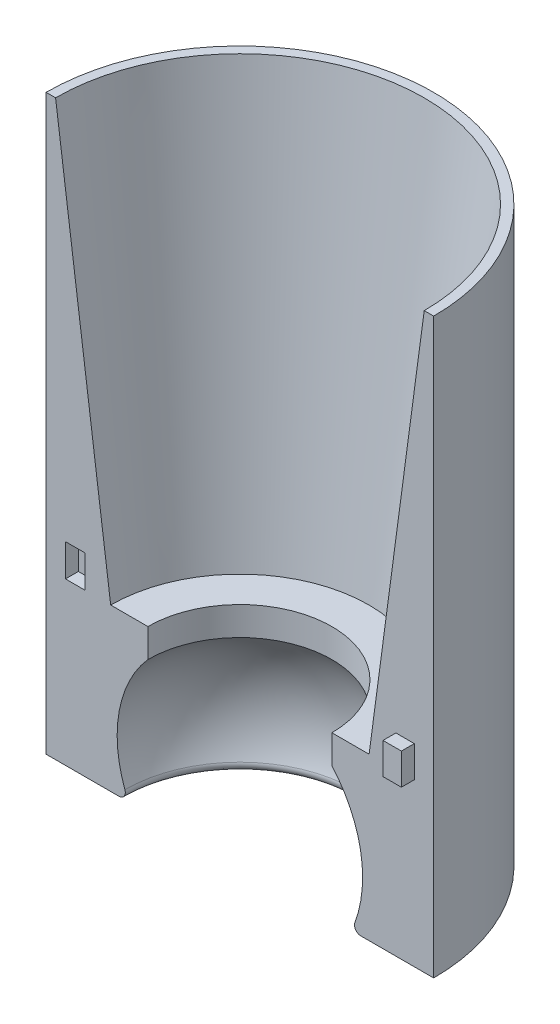
SolidWorks part; units mm, degrees
ref_plane "Front Plane" through (0, 0, 0) normal (0, 0, 1) x (1, 0, 0)
ref_plane "Top Plane" through (0, 0, 0) normal (0, 1, 0) x (1, 0, 0)
ref_plane "Right Plane" through (0, 0, 0) normal (1, 0, 0) x (0, 0, -1)
sketch "Sketch3" plane through (0, 0, 0) normal (0, 0, 1) x (1, 0, 0)
  line L2 (-9.1279, 13.2005) -> (-9.1279, -24.7995)
  line L4 (-9.1279, -13.7995) -> (-39.1279, -13.7995)
  line L5 (-9.1279, -13.7995) -> (-9.1279, 74.9367)
  line L6 (-9.1279, 74.9367) -> (-39.1279, 74.9367)
  line L7 (-39.1279, -13.7995) -> (-39.1279, 74.9367)
  line L8 (-23.3708, 11.2005) -> (-9.1279, 11.2005)
  line L9 (-23.3708, 11.2005) -> (-23.3708, 6.7758)
  line L10 (-9.1279, 95.8585) -> (-9.1279, -91.8555) construction
  line L11 (-23.3708, 11.2005) -> (-29.1283, 11.2005)
  line L12 (-29.1283, 11.2005) -> (-37.6602, 74.9367)
  arc A0 (-9.1279, 13.2005) -> (-9.1279, -24.7995) centre (-9.1279, -5.7995) ccw
  dimension "D5" = 19
  dimension "D1" = 30
  dimension "D2" = 8
  dimension "D3" = 30
  dimension "D4" = 17
revolve "Revolve8" add sketch "Sketch3" angle 180 about L10
sketch "Sketch5" plane through (0, 0, 0) normal (0, 0, 1) x (1, 0, 0)
  line L0 (20.8721, -13.7995) -> (20.8721, 74.9367) construction
  line L1 (15.0221, 16.1255) -> (17.8721, 16.1255)
  line L2 (15.0221, 16.1255) -> (15.0221, 11.2755)
  line L3 (15.0221, 11.2755) -> (17.8721, 11.2755)
  line L4 (17.8721, 16.1255) -> (17.8721, 11.2755)
  line L5 (8.1058, -13.7995) -> (20.8721, -13.7995) construction
  line L6 (17.8721, 13.7005) -> (20.8721, 13.7005) construction
  line L7 (16.4471, 16.1255) -> (16.4471, -13.7995) construction
  line L8 (16.4471, 13.7005) -> (20.8721, 13.7005) construction
  point P13 (16.4471, 13.7005)
  dimension "D2" = 3
  dimension "D3" = 4.85
  dimension "D4" = 2.85
  dimension "D5" = 4.425
  dimension "D6" = 3
extrude "Boss-Extrude1" add sketch "Sketch5" along normal blind 2
sketch "Sketch6" plane through (0, 0, 0) normal (0, 0, 1) x (1, 0, 0)
  line L0 (-26.3616, -13.7995) -> (-39.1279, -13.7995) construction
  line L1 (-36.1279, 16.2005) -> (-33.1279, 16.2005)
  line L2 (-36.1279, 16.2005) -> (-36.1279, 11.2005)
  line L3 (-36.1279, 11.2005) -> (-33.1279, 11.2005)
  line L4 (-33.1279, 16.2005) -> (-33.1279, 11.2005)
  line L5 (-39.1279, -13.7995) -> (-39.1279, 74.9367) construction
  line L6 (-34.6279, 16.2005) -> (-34.6279, -13.7995) construction
  dimension "D1" = 25
  dimension "D2" = 5
  dimension "D3" = 3
  dimension "D4" = 3
extrude "Cut-Extrude1" cut sketch "Sketch6" against normal blind 2
fillet "Fillet1" radius 1 1 edges at (-9.1279, -13.7995, -17.2337)
